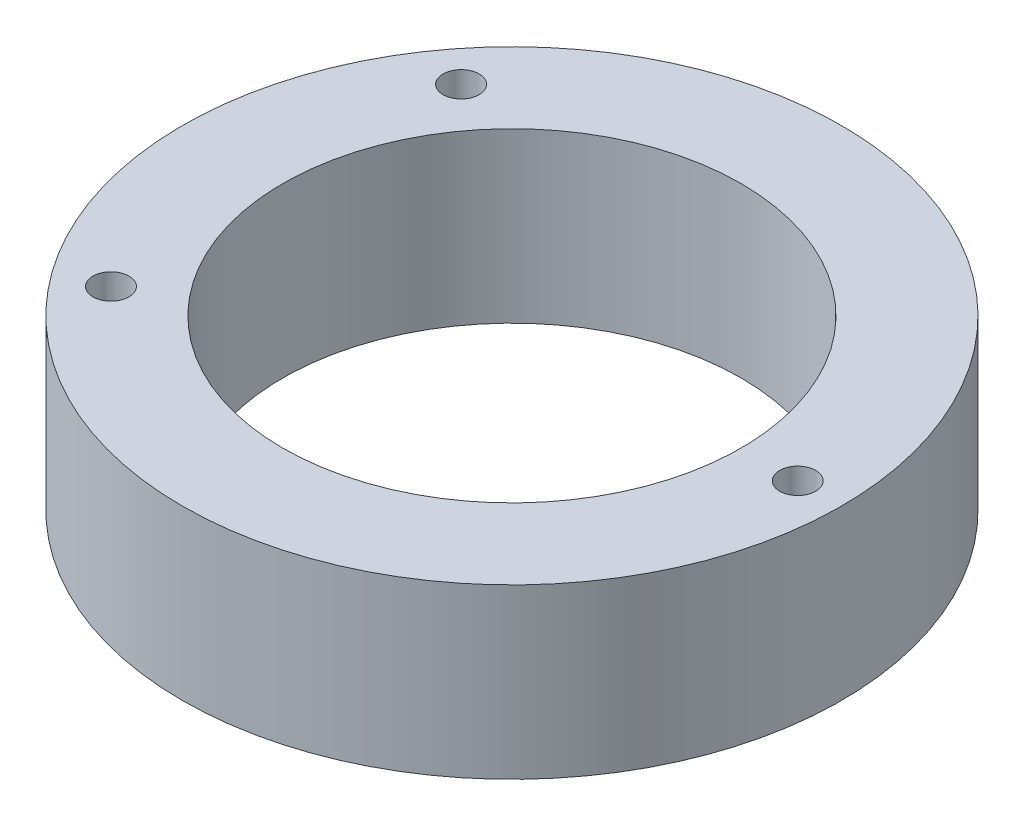
SolidWorks part; units mm, degrees
material "AISI 1020"
ref_plane "Front Plane" through (0, 0, 0) normal (0, 0, 1) x (1, 0, 0)
ref_plane "Top Plane" through (0, 0, 0) normal (0, 1, 0) x (1, 0, 0)
ref_plane "Right Plane" through (0, 0, 0) normal (1, 0, 0) x (0, 0, -1)
sketch "Sketch1" plane through (0, 0, 0) normal (0, 1, 0) x (1, 0, 0)
  line L0 (0, 0) -> (-21.9327, 17.0005) construction
  line L1 (0, 0) -> (-21.9327, -17.0005) construction
  line L2 (0, 0) -> (27.75, 0) construction
  line L3 (-21.9327, 17.0005) -> (-21.9327, -17.0005) construction
  circle A0 centre (0, 0) radius 22.25
  circle A1 centre (0, 0) radius 32
  circle A2 centre (-21.9327, 17.0005) radius 1.75
  circle A3 centre (-21.9327, -17.0005) radius 1.75
  circle A4 centre (27.75, 0) radius 1.75
  dimension "D1" = 64
  dimension "D2" = 44.5
  dimension "D5" = 3.5
  dimension "D3" = 75.56
  dimension "D4" = 27.75
extrude "Boss-Extrude1" add sketch "Sketch1" along normal blind 16.35
